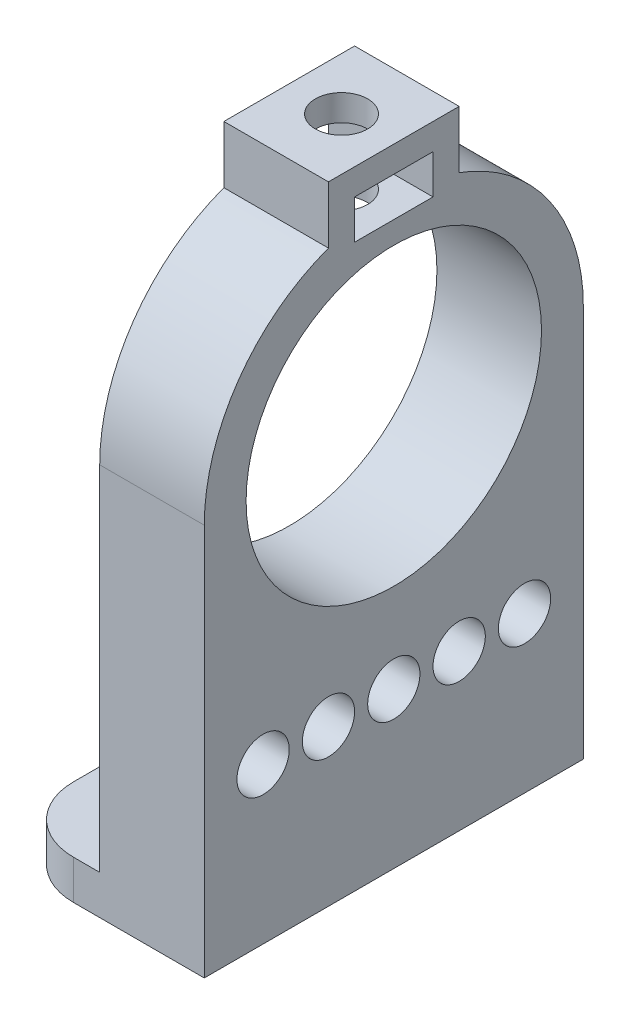
SolidWorks part; units mm, degrees
ref_plane "Front Plane" through (0, 0, 0) normal (0, 0, 1) x (1, 0, 0)
ref_plane "Top Plane" through (0, 0, 0) normal (0, 1, 0) x (1, 0, 0)
ref_plane "Right Plane" through (0, 0, 0) normal (1, 0, 0) x (0, 0, -1)
ref_plane "Plane1" through (0, -2.813, 0) normal (0, -1, 0) x (-1, 0, 0)
ref_plane "Plane2" through (3.7155, 0, 0) normal (-1, 0, 0) x (0, 0, 1)
ref_plane "Plane3" through (14.7155, 0, 0) normal (-1, 0, 0) x (0, 0, 1)
ref_plane "Plane4" through (3.7155, 0, 0) normal (1, 0, 0) x (0, 0, -1)
sketch "Sketch15" plane through (3.7155, 0, 0) normal (1, 0, 0) x (0, 0, -1)
  line L1 (33.1467, -20.713) -> (4.1467, -20.713)
  line L2 (33.1467, 9.287) -> (33.1467, -20.713)
  line L3 (4.1467, 9.287) -> (4.1467, -20.713)
  line L4 (40, -20.713) -> (33.1467, -20.713) construction
  line L5 (4.1467, -20.713) -> (0, -20.713) construction
  arc A2 (33.1467, 9.287) -> (4.1467, 9.287) centre (18.6467, 9.287) ccw
  circle A3 centre (18.6467, 9.287) radius 11.5
  arc A4 (4.1467, 9.287) -> (33.1467, 9.287) centre (18.6467, 9.287) ccw construction
  circle A5 centre (18.6467, 9.287) radius 14.5 construction
  dimension "D2" = 30
  dimension "D1" = 3
extrude "Boss-Extrude8" add sketch "Sketch15" against normal blind 8
sketch "Sketch16" plane through (-4.2845, 0, 0) normal (-1, 0, 0) x (0, 0, 1)
  circle A1 centre (-18.6467, 9.287) radius 11.5 construction
  circle A2 centre (-18.6467, 9.287) radius 11.3
  circle A3 centre (-18.6467, 9.287) radius 11.3
  circle A4 centre (-18.6467, 9.287) radius 11.5
  dimension "D1" = 0.2
extrude "Boss-Extrude9" add sketch "Sketch16" against normal up to surface (8 mm away) up to face at (3.7155, 9.287, -30.1467)
sketch "Sketch17" plane through (-4.2845, 0, 0) normal (-1, 0, 0) x (0, 0, 1)
  line L0 (-18.6467, -20.713) -> (-18.6467, 23.787) construction
  line L1 (-4.1467, -20.713) -> (-33.1467, -20.713) construction
  line L3 (-23.6467, 25.287) -> (-13.6467, 25.287)
  line L4 (-23.6467, 25.287) -> (-23.6467, 22.287)
  line L5 (-23.6467, 22.287) -> (-13.6467, 22.287)
  line L6 (-13.6467, 25.287) -> (-13.6467, 22.287)
  line L7 (-23.6467, 25.287) -> (-13.6467, 22.287) construction
  line L8 (-23.6467, 22.287) -> (-13.6467, 25.287) construction
  arc A0 (-4.1467, 9.287) -> (-33.1467, 9.287) centre (-18.6467, 9.287) ccw construction
  dimension "D1" = 10
  dimension "D2" = 3
extrude "Boss-Extrude10" add sketch "Sketch17" against normal up to surface (8 mm away) up to face at (3.7155, -2.088, -18.6467)
sketch "Sketch18" plane through (0, 25.287, 0) normal (0, 1, 0) x (1, 0, 0)
  line L4 (-4.2845, 13.6467) -> (3.7155, 13.6467)
  line L5 (3.7155, 13.6467) -> (3.7155, 23.6467)
  line L6 (3.7155, 23.6467) -> (-4.2845, 23.6467)
  line L7 (-4.2845, 23.6467) -> (-4.2845, 13.6467)
  line L8 (-4.2845, 13.6467) -> (3.7155, 13.6467)
  line L9 (3.7155, 13.6467) -> (3.7155, 23.6467)
  line L10 (3.7155, 23.6467) -> (-4.2845, 23.6467)
  line L11 (-4.2845, 23.6467) -> (-4.2845, 13.6467)
  dimension "D1" = 0
extrude "Boss-Extrude11" add sketch "Sketch18" along normal blind 2
sketch "Sketch19" plane through (-4.2845, 0, 0) normal (-1, 0, 0) x (0, 0, 1)
  line L0 (-18.6467, 27.287) -> (-18.6467, 20.587) construction
  line L1 (-23.6467, 27.287) -> (-13.6467, 27.287) construction
  line L3 (-21.6467, 25.287) -> (-15.6467, 25.287)
  line L4 (-21.6467, 25.287) -> (-21.6467, 22.287)
  line L5 (-21.6467, 22.287) -> (-15.6467, 22.287)
  line L6 (-15.6467, 25.287) -> (-15.6467, 22.287)
  line L7 (-21.6467, 25.287) -> (-15.6467, 22.287) construction
  line L8 (-21.6467, 22.287) -> (-15.6467, 25.287) construction
  circle A0 centre (-18.6467, 9.287) radius 11.3 construction
  point P6 (-18.6467, 23.787)
  dimension "D1" = 6
  dimension "D2" = 3
  dimension "D3" = 3.2
extrude "Cut-Extrude4" cut sketch "Sketch19" against normal up to surface (8 mm away) up to face at (3.7155, 10.0631, -18.6467)
sketch "Sketch20" plane through (0, 27.287, 0) normal (0, 1, 0) x (1, 0, 0)
  line L0 (-0.2845, 23.6467) -> (-0.2845, 13.6467) construction
  line L1 (3.7155, 23.6467) -> (-4.2845, 23.6467) construction
  line L2 (-4.2845, 13.6467) -> (3.7155, 13.6467) construction
  circle A0 centre (-0.2845, 18.6467) radius 2
  dimension "D1" = 4
extrude "Cut-Extrude5" cut sketch "Sketch20" against normal blind 9
sketch "Sketch21" plane through (-4.2845, 0, 0) normal (-1, 0, 0) x (0, 0, 1)
  line L0 (-4.1467, 9.287) -> (-4.1467, -20.713) construction
  line L1 (-33.1467, -20.713) -> (-4.1467, -20.713)
  line L2 (-33.1467, -20.713) -> (-33.1467, -17.713)
  line L3 (-33.1467, -17.713) -> (-4.1467, -17.713)
  line L4 (-4.1467, -20.713) -> (-4.1467, -17.713)
  line L5 (-33.1467, -20.713) -> (-33.1467, 9.287) construction
  line L6 (-4.1467, -20.713) -> (-33.1467, -20.713) construction
  dimension "D1" = 3
extrude "Boss-Extrude12" add sketch "Sketch21" along normal blind 7
sketch "Sketch22" plane through (0, -17.713, 0) normal (0, 1, 0) x (1, 0, 0)
  line L0 (-11.2845, 18.6467) -> (-4.2845, 18.6467) construction
  line L1 (-11.2845, 4.1467) -> (-11.2845, 33.1467) construction
  line L2 (-4.2845, 23.6467) -> (-4.2845, 13.6467) construction
  line L3 (-7.7845, 4.1467) -> (-7.7845, 18.6467) construction
  line L4 (-11.2845, 4.1467) -> (-4.2845, 4.1467) construction
  line L5 (-7.7845, 18.6467) -> (-7.7845, 33.1467) construction
  line L6 (-11.2845, 33.1467) -> (-4.2845, 33.1467) construction
  circle A0 centre (-7.7845, 11.3967) radius 2
  circle A1 centre (-7.7845, 18.6467) radius 2
  circle A2 centre (-7.7845, 25.8967) radius 2
  dimension "D1" = 4
  dimension "D2" = 4
  dimension "D3" = 4
extrude "Cut-Extrude6" cut sketch "Sketch22" against normal blind 7
fillet "Fillet1" radius 5 2 edges at (-11.2845, -19.213, -33.1467) (-11.2845, -19.213, -4.1467)
sketch "Sketch24" plane through (-4.2845, 0, 0) normal (-1, 0, 0) x (0, 0, 1)
  line L1 (-38.8136, -6.713) -> (1.5202, -6.713) construction
  line L2 (-18.6467, -6.713) -> (-18.6467, -17.713) construction
  line L3 (-9.1467, -17.713) -> (-28.1467, -17.713) construction
  line L4 (-33.1467, -8.813) -> (-18.6467, -8.813) construction
  line L5 (-33.1467, -17.713) -> (-33.1467, 9.287) construction
  line L6 (-18.6467, -8.813) -> (-4.1467, -8.813) construction
  line L7 (-4.1467, 9.287) -> (-4.1467, -17.713) construction
  circle A0 centre (-18.6467, -8.813) radius 2
  circle A1 centre (-13.6467, -8.813) radius 2
  circle A2 centre (-23.6467, -8.813) radius 2
  circle A3 centre (-28.6467, -8.813) radius 2
  circle A4 centre (-8.6467, -8.813) radius 2
  dimension "D2" = 4
  dimension "D3" = 4
  dimension "D4" = 4
  dimension "D7" = 4
  dimension "D8" = 4
  dimension "D1" = 2.1
  dimension "D5" = 5
  dimension "D6" = 5
  dimension "D9" = 5
  dimension "D10" = 5
extrude "Cut-Extrude10" cut sketch "Sketch24" against normal up to surface (8 mm away) up to face at (3.7155, 23.787, -18.6467)
